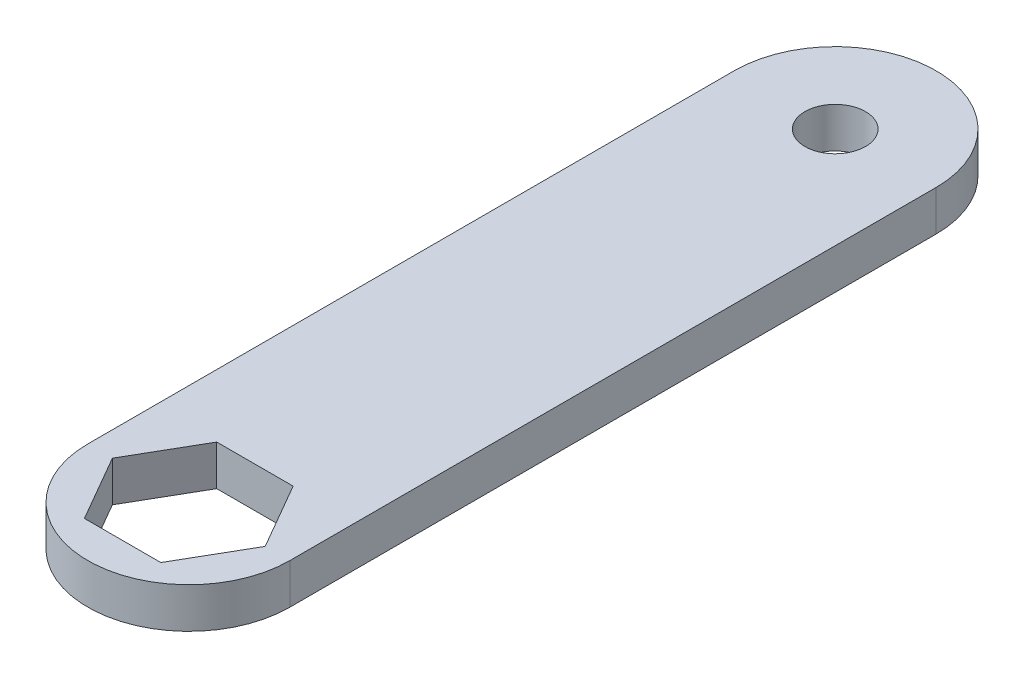
SolidWorks part; units mm, degrees
ref_plane "前视基准面" through (0, 0, 0) normal (0, 0, 1) x (1, 0, 0)
ref_plane "上视基准面" through (0, 0, 0) normal (0, 1, 0) x (1, 0, 0)
ref_plane "右视基准面" through (0, 0, 0) normal (1, 0, 0) x (0, 0, -1)
sketch "草图1" plane through (0, 0, 0) normal (0, 1, 0) x (1, 0, 0)
  line L0 (0, -16) -> (0, 16) construction
  line L1 (-5, -16) -> (-5, 16)
  line L2 (5, -16) -> (5, 16)
  line L3 (-1000, 0) -> (49000, 0) construction
  line L5 (1.8908, -12.725) -> (-1.8908, -12.725)
  line L6 (-1.8908, -12.725) -> (-3.7816, -16)
  line L7 (-3.7816, -16) -> (-1.8908, -19.275)
  line L8 (-1.8908, -19.275) -> (1.8908, -19.275)
  line L9 (1.8908, -19.275) -> (3.7816, -16)
  line L10 (3.7816, -16) -> (1.8908, -12.725)
  arc A0 (-5, -16) -> (5, -16) centre (0, -16) ccw
  arc A1 (5, 16) -> (-5, 16) centre (0, 16) ccw
  circle A2 centre (0, 16) radius 1.5
  circle A4 centre (0, -16) radius 3.275 construction
  point P3 (0, 0)
  dimension "D3" = 3
  dimension "D4" = 6.55
  dimension "D1" = 32
  dimension "D2" = 10
extrude "凸台-拉伸1" add sketch "草图1" along normal blind 2
